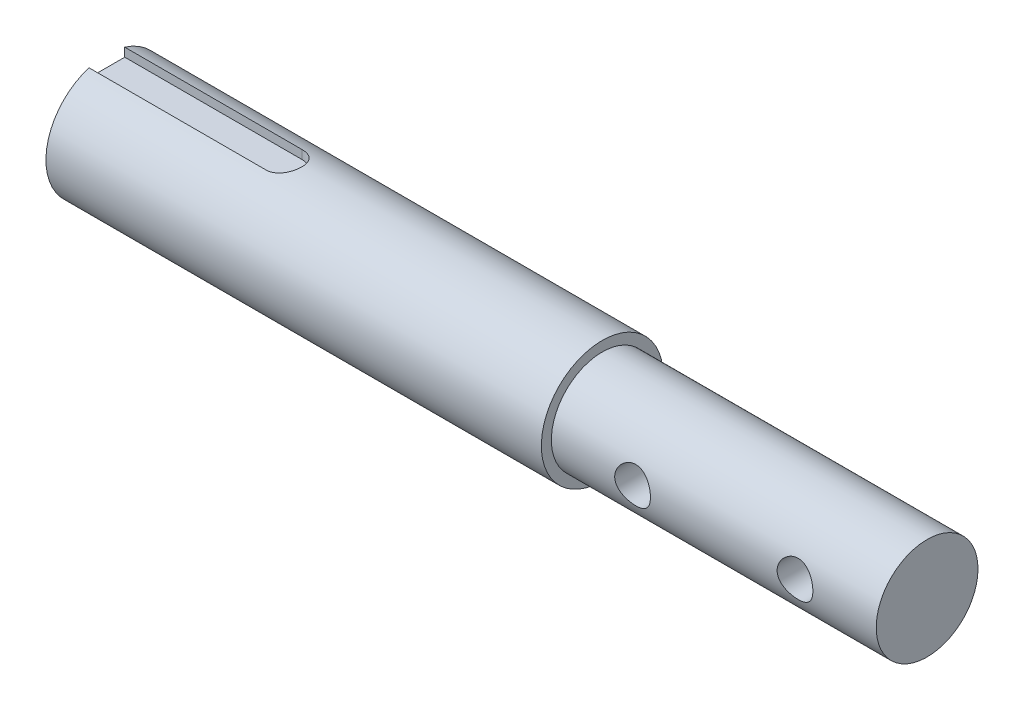
SolidWorks part; units mm, degrees
material "ASTM A36 Steel"
ref_plane "Front Plane" through (0, 0, 0) normal (0, 0, 1) x (1, 0, 0)
ref_plane "Top Plane" through (0, 0, 0) normal (0, 1, 0) x (1, 0, 0)
ref_plane "Right Plane" through (0, 0, 0) normal (1, 0, 0) x (0, 0, -1)
sketch "Sketch1" plane through (0, 0, 0) normal (1, 0, 0) x (0, 0, -1)
  circle A0 centre (0, 0) radius 37.5
  dimension "D1" = 75
extrude "Boss-Extrude1" add sketch "Sketch1" along normal blind 305
sketch "Sketch2" plane through (305, 0, 0) normal (1, 0, 0) x (0, 0, -1)
  circle A0 centre (0, 0) radius 31.34
  dimension "D1" = 62.68
extrude "Boss-Extrude2" add sketch "Sketch2" along normal blind 200
ref_plane "Plane1" through (0, 37.5, 0) normal (0, 1, 0) x (1, 0, 0)
sketch "Sketch3" plane through (0, 37.5, 0) normal (0, 1, 0) x (1, 0, 0)
  line L0 (0, 37.5) -> (0, -37.5) construction
  line L1 (109, -11) -> (0, -11)
  line L2 (0, -11) -> (0, 11)
  line L3 (0, 11) -> (109, 11)
  arc A0 (109, -11) -> (109, 11) centre (109, 0) ccw
  dimension "D1" = 22
  dimension "D2" = 109
extrude "Cut-Extrude1" cut sketch "Sketch3" against normal blind 7
sketch "Sketch4" plane through (0, 0, 0) normal (0, 0, 1) x (1, 0, 0)
  line L0 (305, -37.5) -> (305, 37.5) construction
  circle A0 centre (355, 0) radius 11
  circle A1 centre (455, 0) radius 11
  dimension "D1" = 22
  dimension "D2" = 22
  dimension "D3" = 50
  dimension "D4" = 100
extrude "Cut-Extrude2" cut sketch "Sketch4" against normal through all both and the other way through all
